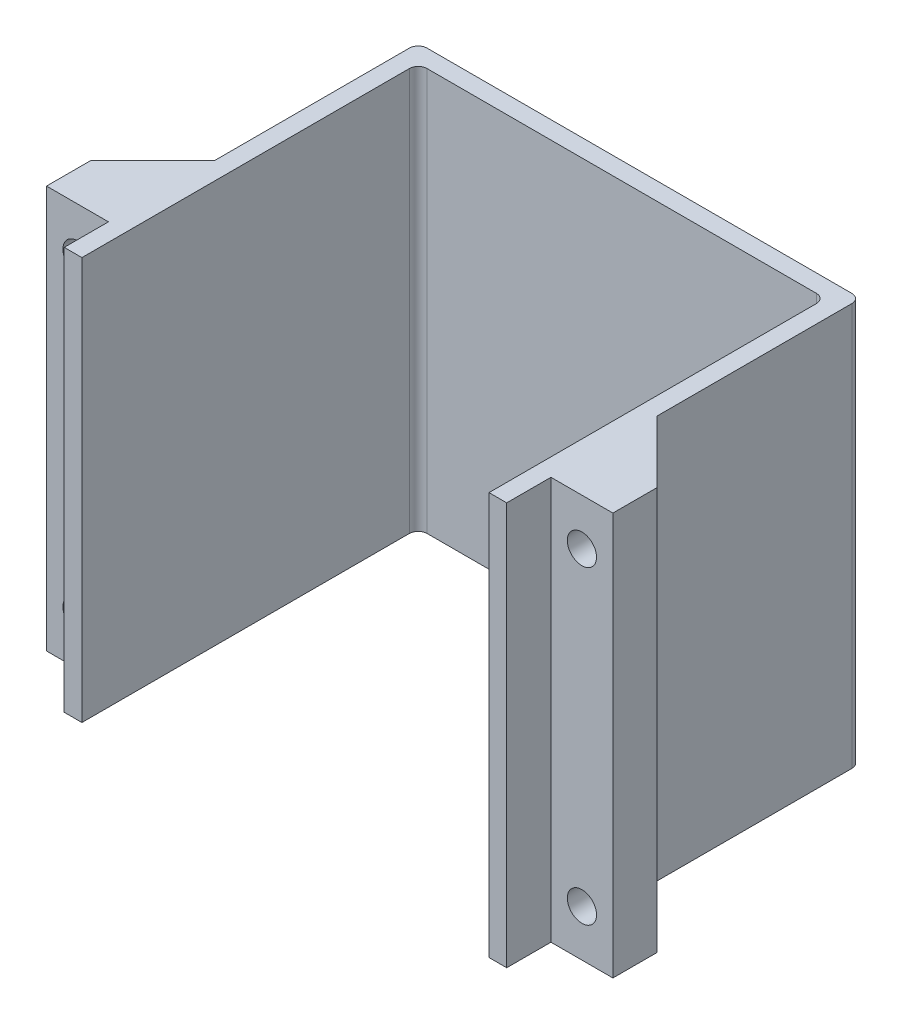
SolidWorks part; units mm, degrees
ref_plane "前视基准面" through (0, 0, 0) normal (0, 0, 1) x (1, 0, 0)
ref_plane "上视基准面" through (0, 0, 0) normal (0, 1, 0) x (1, 0, 0)
ref_plane "右视基准面" through (0, 0, 0) normal (1, 0, 0) x (0, 0, -1)
sketch "草图1" plane through (0, 0, 0) normal (0, 1, 0) x (1, 0, 0)
  line L1 (-32, 20) -> (32, 20)
  line L2 (-32, 20) -> (-32, -20)
  line L3 (-32, -20) -> (32, -20)
  line L4 (32, 20) -> (32, -20)
  line L5 (-32, 20) -> (32, -20) construction
  line L6 (-32, -20) -> (32, 20) construction
  point P0 (0, 0)
  dimension "D1" = 64
  dimension "D2" = 40
extrude "凸台-拉伸1" add sketch "草图1" along normal blind 45.5
sketch "草图2" plane through (0, 45.5, 0) normal (0, 1, 0) x (1, 0, 0)
  line L0 (-32, -20) -> (32, -20) construction
  line L1 (23, 18) -> (-23, 18)
  line L2 (23, 18) -> (23, -20)
  line L3 (23, -20) -> (-23, -20)
  line L4 (-23, 18) -> (-23, -20)
  line L5 (23, 18) -> (-23, -20) construction
  line L6 (23, -20) -> (-23, 18) construction
  line L7 (0, -1) -> (0, 0) construction
  point P0 (0, -1)
  dimension "D1" = 46
  dimension "D2" = 38
extrude "切除-拉伸1" cut sketch "草图2" against normal up to next
sketch "草图3" plane through (0, 45.5, 0) normal (0, 1, 0) x (1, 0, 0)
  line L0 (0, 18) -> (0, 20) construction
  line L1 (-32, 20) -> (-25, 20)
  line L2 (-32, 20) -> (-32, -10)
  line L3 (-32, -10) -> (-25, -10)
  line L4 (-25, 20) -> (-25, -10)
  line L5 (23, 18) -> (-23, 18) construction
  line L6 (32, 20) -> (-32, 20) construction
  line L7 (-25, 5) -> (-23, 5) construction
  line L8 (-23, 18) -> (-23, -20) construction
  line L9 (-32, -20) -> (-23, -20) construction
  dimension "D1" = 10
extrude "切除-拉伸2" cut sketch "草图3" against normal up to next
sketch "草图6" plane through (0, 0, 0) normal (0, 1, 0) x (1, 0, 0)
  line L0 (-32, -10) -> (-25, -10)
  line L1 (-25, -10) -> (-25, -3)
  line L2 (-25, -10) -> (-25, 20) construction
  line L3 (-25, -3) -> (-32, -10)
  dimension "D1" = 45
extrude "凸台-拉伸2" add sketch "草图6" along normal up to surface (45.5 mm away) up to face at (-5, 45.5, 2.4)
sketch "草图4" plane through (0, 0, 20) normal (0, 0, -1) x (-1, 0, 0)
  line L0 (25, 22.75) -> (32, 22.75) construction
  line L3 (28.5, 40.25) -> (28.5, 5.25) construction
  line L4 (32, 45.5) -> (32, 0) construction
  line L5 (25, 45.5) -> (25, 0) construction
  circle A0 centre (28.5, 40.25) radius 1.65
  circle A1 centre (28.5, 5.25) radius 1.65
  point P2 (25, 22.75)
  point P4 (31, 22.75)
  point P9 (28.5, 22.75)
  dimension "D2" = 3.3
  dimension "D1" = 35
extrude "切除-拉伸3" cut sketch "草图4" along normal up to next
sketch "草图7" plane through (0, 0, -20) normal (0, 0, -1) x (-1, 0, 0)
  circle A0 centre (28.5, 40.25) radius 3
  circle A1 centre (28.5, 5.25) radius 3
  dimension "D1" = 6
extrude "切除-拉伸4" cut sketch "草图7" against normal offset from surface (30 mm away) 10 up to face at (-30.15, 40.25, 20)
sketch "草图8" plane through (0, 0, 20) normal (0, 0, 1) x (1, 0, 0)
  line L0 (22, 0) -> (-22, 0) construction
  line L1 (-32, 45.5) -> (-25, 45.5)
  line L2 (-32, 45.5) -> (-32, 0)
  line L3 (-32, 0) -> (-25, 0)
  line L4 (-25, 45.5) -> (-25, 0)
  line L5 (-25, 45.5) -> (-25, 0) construction
extrude "切除-拉伸5" cut sketch "草图8" against normal blind 5
mirror "镜向1" about plane through (0, 0, 0) normal (1, 0, 0) of "切除-拉伸5", "切除-拉伸2", "凸台-拉伸2", "切除-拉伸4", "切除-拉伸3"
fillet "圆角1" radius 1 4 edges at (-25, 22.75, -20) (-23, 22.75, -18) (25, 22.75, -20) (23, 22.75, -18)
